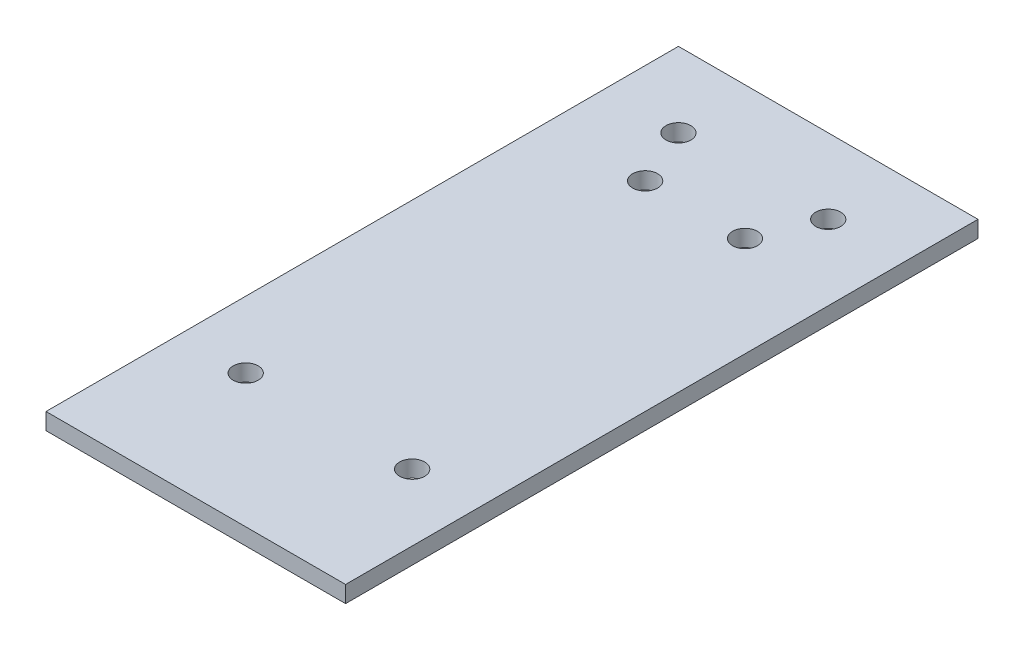
SolidWorks part; units mm, degrees
ref_plane "Front Plane" through (0, 0, 0) normal (0, 0, 1) x (1, 0, 0)
ref_plane "Top Plane" through (0, 0, 0) normal (0, 1, 0) x (1, 0, 0)
ref_plane "Right Plane" through (0, 0, 0) normal (1, 0, 0) x (0, 0, -1)
sketch "Sketch3" plane through (0, 0, 0) normal (0, 1, 0) x (1, 0, 0)
  line L0 (0, 230.8) -> (0, 0) construction
  line L1 (70, 30) -> (70, 10)
  line L2 (45, 35) -> (65, 35)
  line L3 (45, 103) -> (45, 35)
  line L4 (60, 103) -> (45, 103)
  line L5 (70, 147) -> (70, 113)
  line L6 (45, 157) -> (60, 157)
  line L7 (45, 225) -> (45, 157)
  line L8 (65.0644, 225) -> (45, 225)
  line L9 (70, 245) -> (70, 229.2)
  line L274 (57.35, 260) -> (-57.35, 260)
  line L284 (-70, 245) -> (-70, 229.2)
  line L295 (-65.0644, 225) -> (-45, 225)
  line L296 (-45, 225) -> (-45, 157)
  line L297 (-45, 157) -> (-60, 157)
  line L308 (-70, 147) -> (-70, 113)
  line L319 (-60, 103) -> (-45, 103)
  line L320 (-45, 103) -> (-45, 35)
  line L321 (-45, 35) -> (-65, 35)
  line L332 (-70, 30) -> (-70, 10)
  line L342 (-60, 0) -> (60, 0)
  arc A0 (-57.35, 260) -> (-70, 245) centre (-55.0011, 245.185) ccw
  arc A1 (-70, 229.2) -> (-65.0644, 225) centre (-65.0644, 230) ccw
  arc A2 (-60, 157) -> (-70, 147) centre (-60, 147) ccw
  arc A3 (-70, 113) -> (-60, 103) centre (-60, 113) ccw
  arc A4 (-65, 35) -> (-70, 30) centre (-65, 30) ccw
  arc A5 (-70, 10) -> (-60, 0) centre (-60, 10) ccw
  arc A6 (70, 10) -> (60, 0) centre (60, 10) cw
  arc A7 (65, 35) -> (70, 30) centre (65, 30) cw
  arc A8 (70, 113) -> (60, 103) centre (60, 113) cw
  arc A9 (60, 157) -> (70, 147) centre (60, 147) cw
  arc A10 (70, 229.2) -> (65.0644, 225) centre (65.0644, 230) cw
  arc A11 (57.35, 260) -> (70, 245) centre (55.0011, 245.185) cw
  point P42 (0, 0)
  point P46 (0, 260)
  dimension "D2" = 15
  dimension "D3" = 5
  dimension "D5" = 5
  dimension "D6" = 10
  dimension "D7" = 10
  dimension "D8" = 10
  dimension "D4" = 45
  dimension "D1" = 57.35
  dimension "D9" = 15.8
  dimension "D10" = 260
  dimension "D11" = 35
  dimension "D12" = 15
  dimension "D14" = 68
  dimension "D15" = 68
  dimension "D16" = 35
  dimension "D17" = 54
  dimension "D18" = 140
  dimension "D19" = 25
extrude "Boss-Extrude2" add sketch "Sketch3" along normal mid plane 5 separate body
sketch "Sketch4" plane through (0, 2.5, 0) normal (0, 1, 0) x (1, 0, 0)
  line L0 (-70, 122) -> (-98.1217, 122) construction
  line L5 (60, 157) -> (45, 157) construction
  line L6 (-6, 203.75) -> (6, 203.75)
  line L7 (-6, 203.75) -> (-6, 226.25)
  line L8 (-6, 226.25) -> (6, 226.25)
  line L9 (6, 203.75) -> (6, 226.25)
  line L10 (-6, 203.75) -> (6, 226.25) construction
  line L11 (-6, 226.25) -> (6, 203.75) construction
  line L12 (0, 230.8) -> (0, 242.4267) construction
  line L13 (45, 157) -> (45, 225) construction
  line L14 (57.35, 260) -> (-57.35, 260) construction
  line L15 (-70, 245) -> (-70, 229.2) construction
  line L16 (45, 225) -> (65.0644, 225) construction
  line L17 (-45, 157) -> (-60, 157) construction
  line L18 (-6, 17.75) -> (6, 40.25) construction
  line L19 (-70, 147) -> (-70, 113) construction
  line L20 (-6, 40.25) -> (6, 17.75) construction
  line L21 (6, 40.25) -> (6, 17.75)
  line L22 (-6, 17.75) -> (6, 17.75)
  line L23 (-6, 40.25) -> (-6, 17.75)
  line L24 (-6, 40.25) -> (6, 40.25)
  circle A0 centre (-40, 252.5) radius 5
  circle A1 centre (-20, 252.5) radius 5
  circle A2 centre (-16, 212.5) radius 5
  circle A3 centre (16, 212.5) radius 5
  circle A4 centre (0, 231.25) radius 2.5
  circle A5 centre (0, 198.75) radius 2.5
  circle A6 centre (-30, 152) radius 10
  circle A7 centre (30, 152) radius 10
  circle A8 centre (-15, 137) radius 5
  circle A9 centre (15, 137) radius 5
  circle A10 centre (-62.5, 122) radius 5
  circle A11 centre (62.5, 122) radius 5
  circle A12 centre (20, 252.5) radius 5
  circle A13 centre (40, 252.5) radius 5
  circle A14 centre (40, -8.5) radius 5
  circle A15 centre (20, -8.5) radius 5
  circle A16 centre (15, 107) radius 5
  circle A17 centre (-15, 107) radius 5
  circle A18 centre (30, 92) radius 10
  circle A19 centre (-30, 92) radius 10
  circle A20 centre (0, 45.25) radius 2.5
  circle A21 centre (0, 12.75) radius 2.5
  circle A22 centre (16, 31.5) radius 5
  circle A23 centre (-16, 31.5) radius 5
  circle A24 centre (-20, -8.5) radius 5
  circle A25 centre (-40, -8.5) radius 5
  point P0 (0, 215)
  point P82 (0, 29)
  dimension "D3" = 10
  dimension "D10" = 15
  dimension "D14" = 20
  dimension "D18" = 5
  dimension "D1" = 12
  dimension "D2" = 22.5
  dimension "D4" = 20
  dimension "D5" = 20
  dimension "D6" = 7.5
  dimension "D7" = 30
  dimension "D8" = 35
  dimension "D9" = 7.5
  dimension "D11" = 15
  dimension "D12" = 5
  dimension "D13" = 15
  dimension "D15" = 10
  dimension "D16" = 12.5
  dimension "D17" = 10
  dimension "D19" = 5
  dimension "D20" = 5
extrude "Cut-Extrude1" [suppressed] cut sketch "Sketch4" against normal up to surface (5 mm away)
sketch "Sketch5" plane through (0, 2.5, 0) normal (0, 1, 0) x (1, 0, 0)
  line L0 (-45, 35) -> (45, 35) construction
  line L1 (-45, 225) -> (45, 225) construction
  line L2 (-45, 103) -> (-45, 35) construction
  line L3 (0, 0) -> (0, 96.1149) construction
  circle A0 centre (-25, 75) radius 3.75
  circle A1 centre (-22.5, 202.5) radius 3.75
  circle A2 centre (-15, 185) radius 3.75
  circle A3 centre (25, 75) radius 3.75
  circle A4 centre (15, 185) radius 3.75
  circle A5 centre (22.5, 202.5) radius 3.75
  dimension "D3" = 7.5
  dimension "D5" = 40
  dimension "D1" = 20
  dimension "D2" = 40
  dimension "D4" = 22.5
  dimension "D6" = 15
  dimension "D7" = 22.5
extrude "Cut-Extrude2" cut sketch "Sketch5" against normal up to surface (5 mm away) up to face at (0, -2.5, -129.6632)
sketch "Sketch6" plane through (0, 2.5, 0) normal (0, 1, 0) x (1, 0, 0)
  line L0 (-45, 225) -> (45, 225)
  line L1 (-45, 157) -> (-45, 103)
  line L2 (45, 157) -> (45, 103)
  line L3 (-45, 35) -> (45, 35)
  line L20 (-70, 245) -> (-70, 229.2)
  line L21 (-65.0644, 225) -> (-45, 225)
  line L22 (-45, 225) -> (-45, 157)
  line L23 (-45, 157) -> (-60, 157)
  line L24 (-70, 147) -> (-70, 113)
  line L25 (-60, 103) -> (-45, 103)
  line L26 (-45, 103) -> (-45, 35)
  line L27 (-45, 35) -> (-65, 35)
  line L28 (-70, 30) -> (-70, 10)
  line L29 (-60, 0) -> (60, 0)
  line L30 (70, 10) -> (70, 30)
  line L31 (65, 35) -> (45, 35)
  line L32 (45, 35) -> (45, 103)
  line L33 (45, 103) -> (60, 103)
  line L34 (70, 113) -> (70, 147)
  line L35 (60, 157) -> (45, 157)
  line L36 (45, 157) -> (45, 225)
  line L37 (45, 225) -> (65.0644, 225)
  line L38 (70, 229.2) -> (70, 245)
  line L39 (57.35, 260) -> (-57.35, 260)
  line L40 (-70, 245) -> (-70, 229.2)
  line L41 (-65.0644, 225) -> (-45, 225)
  line L42 (-45, 225) -> (-45, 157)
  line L43 (-45, 157) -> (-60, 157)
  line L44 (-70, 147) -> (-70, 113)
  line L45 (-60, 103) -> (-45, 103)
  line L46 (-45, 103) -> (-45, 35)
  line L47 (-45, 35) -> (-65, 35)
  line L48 (-70, 30) -> (-70, 10)
  line L49 (-60, 0) -> (60, 0)
  line L50 (70, 10) -> (70, 30)
  line L51 (65, 35) -> (45, 35)
  line L52 (45, 35) -> (45, 103)
  line L53 (45, 103) -> (60, 103)
  line L54 (70, 113) -> (70, 147)
  line L55 (60, 157) -> (45, 157)
  line L56 (45, 157) -> (45, 225)
  line L57 (45, 225) -> (65.0644, 225)
  line L58 (70, 229.2) -> (70, 245)
  line L59 (57.35, 260) -> (-57.35, 260)
  arc A12 (-57.35, 260) -> (-70, 245) centre (-55.0011, 245.185) ccw
  arc A13 (-70, 229.2) -> (-65.0644, 225) centre (-65.0644, 230) ccw
  arc A14 (-60, 157) -> (-70, 147) centre (-60, 147) ccw
  arc A15 (-70, 113) -> (-60, 103) centre (-60, 113) ccw
  arc A16 (-65, 35) -> (-70, 30) centre (-65, 30) ccw
  arc A17 (-70, 10) -> (-60, 0) centre (-60, 10) ccw
  arc A18 (60, 0) -> (70, 10) centre (60, 10) ccw
  arc A19 (70, 30) -> (65, 35) centre (65, 30) ccw
  arc A20 (60, 103) -> (70, 113) centre (60, 113) ccw
  arc A21 (70, 147) -> (60, 157) centre (60, 147) ccw
  arc A22 (65.0644, 225) -> (70, 229.2) centre (65.0644, 230) ccw
  arc A23 (70, 245) -> (57.35, 260) centre (55.0011, 245.185) ccw
  arc A24 (-57.35, 260) -> (-70, 245) centre (-55.0011, 245.185) ccw
  arc A25 (-70, 229.2) -> (-65.0644, 225) centre (-65.0644, 230) ccw
  arc A26 (-60, 157) -> (-70, 147) centre (-60, 147) ccw
  arc A27 (-70, 113) -> (-60, 103) centre (-60, 113) ccw
  arc A28 (-65, 35) -> (-70, 30) centre (-65, 30) ccw
  arc A29 (-70, 10) -> (-60, 0) centre (-60, 10) ccw
  arc A30 (60, 0) -> (70, 10) centre (60, 10) ccw
  arc A31 (70, 30) -> (65, 35) centre (65, 30) ccw
  arc A32 (60, 103) -> (70, 113) centre (60, 113) ccw
  arc A33 (70, 147) -> (60, 157) centre (60, 147) ccw
  arc A34 (65.0644, 225) -> (70, 229.2) centre (65.0644, 230) ccw
  arc A35 (70, 245) -> (57.35, 260) centre (55.0011, 245.185) ccw
  arc M39 (-57.35, 260) -> (-70, 245) centre (-55.0011, 245.185) ccw
  line M40 (-70, 245) -> (-70, 229.2)
  arc M41 (-70, 229.2) -> (-65.0644, 225) centre (-65.0644, 230) ccw
  line M42 (-65.0644, 225) -> (-45, 225)
  line M44 (-45, 157) -> (-60, 157)
  arc M45 (-60, 157) -> (-70, 147) centre (-60, 147) ccw
  line M46 (-70, 147) -> (-70, 113)
  arc M47 (-70, 113) -> (-60, 103) centre (-60, 113) ccw
  line M48 (-60, 103) -> (-45, 103)
  line M50 (-45, 35) -> (-65, 35)
  arc M51 (-65, 35) -> (-70, 30) centre (-65, 30) ccw
  line M52 (-70, 30) -> (-70, 10)
  arc M53 (-70, 10) -> (-60, 0) centre (-60, 10) ccw
  line M54 (-60, 0) -> (60, 0)
  arc M55 (60, 0) -> (70, 10) centre (60, 10) ccw
  line M56 (70, 10) -> (70, 30)
  arc M57 (70, 30) -> (65, 35) centre (65, 30) ccw
  line M58 (65, 35) -> (45, 35)
  line M60 (45, 103) -> (60, 103)
  arc M61 (60, 103) -> (70, 113) centre (60, 113) ccw
  line M62 (70, 113) -> (70, 147)
  arc M63 (70, 147) -> (60, 157) centre (60, 147) ccw
  line M64 (60, 157) -> (45, 157)
  line M66 (45, 225) -> (65.0644, 225)
  arc M67 (65.0644, 225) -> (70, 229.2) centre (65.0644, 230) ccw
  line M68 (70, 229.2) -> (70, 245)
  arc M69 (70, 245) -> (57.35, 260) centre (55.0011, 245.185) ccw
  line M70 (57.35, 260) -> (-57.35, 260)
  dimension "D1" = 0
extrude "Cut-Extrude3" cut sketch "Sketch6" against normal blind 10 contours L1 M44 M45 M46 M47 M48 | L3 M50 M51 M52 M53 M54 M55 M56 M57 M58 | L2 M64 M60 M61 M62 M63 | L0 M42 M66 M67 M68 M69 M70 M39 M40 M41
